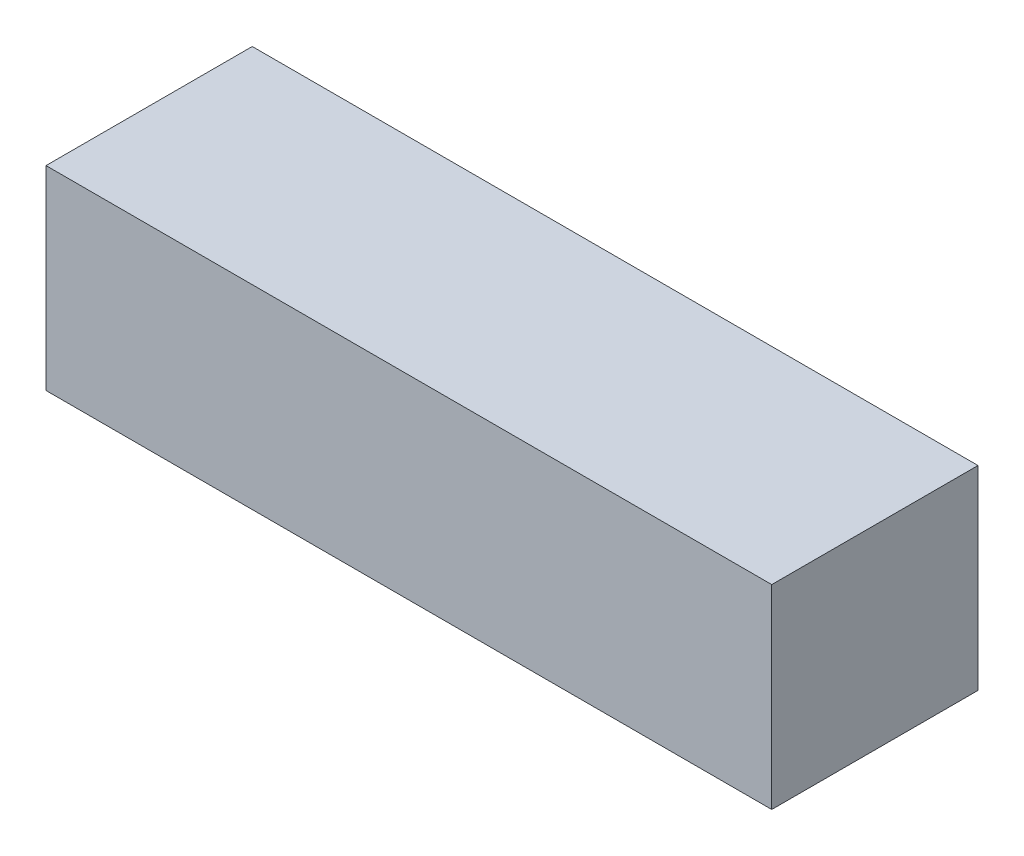
SolidWorks part; units mm, degrees
ref_plane "Front Plane" through (0, 0, 0) normal (0, 0, 1) x (1, 0, 0)
ref_plane "Top Plane" through (0, 0, 0) normal (0, 1, 0) x (1, 0, 0)
ref_plane "Right Plane" through (0, 0, 0) normal (1, 0, 0) x (0, 0, -1)
sketch "Sketch1" plane through (0, 0, 0) normal (0, 1, 0) x (1, 0, 0)
  line L1 (-9.5, -2.7) -> (9.5, -2.7)
  line L2 (-9.5, -2.7) -> (-9.5, 2.7)
  line L3 (-9.5, 2.7) -> (9.5, 2.7)
  line L4 (9.5, -2.7) -> (9.5, 2.7)
  line L5 (-9.5, -2.7) -> (9.5, 2.7) construction
  line L6 (-9.5, 2.7) -> (9.5, -2.7) construction
  point P0 (0, 0)
  dimension "D1" = 19
  dimension "D2" = 5.4
extrude "Boss-Extrude1" add sketch "Sketch1" along normal blind 5.1
sketch "Header-Origin Dimension" plane through (0, 0, 0) normal (0, 1, 0) x (1, 0, 0)
  line L0 (0, 0) -> (0, -9.0074) construction
  line L1 (0, 16.8176) -> (0, -34.8324) construction
  dimension "D1" = 9.0074
sketch3d "3DSketch1"
  line L0 (0, 0, 0) -> (0, 25.0626, 0) construction
  dimension "D1" = 25.0626
